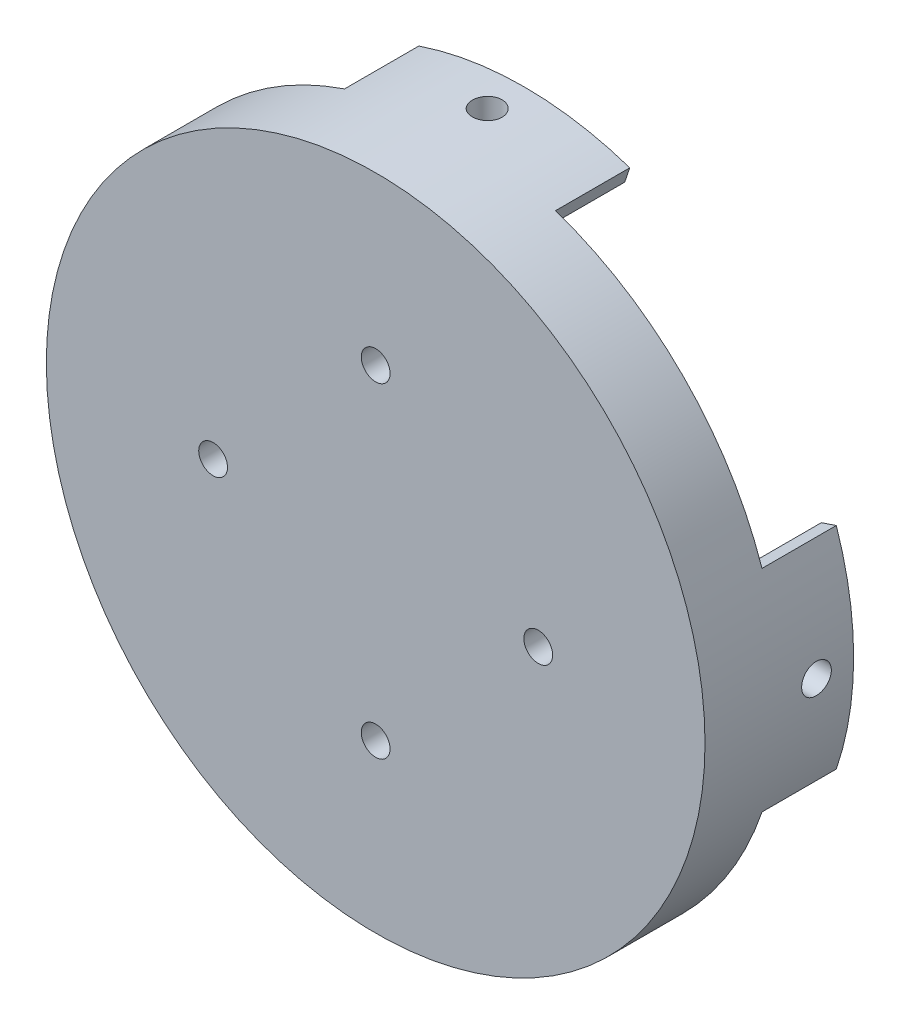
SolidWorks part; units mm, degrees
ref_plane "Front Plane" through (0, 0, 0) normal (0, 0, 1) x (1, 0, 0)
ref_plane "Top Plane" through (0, 0, 0) normal (0, 1, 0) x (1, 0, 0)
ref_plane "Right Plane" through (0, 0, 0) normal (1, 0, 0) x (0, 0, -1)
sketch "Sketch2" plane through (0, 0, 0) normal (0, 0, 1) x (1, 0, 0)
  circle A0 centre (0, 0) radius 45.0259
  circle A1 centre (0, -22.225) radius 1.9685
  circle A2 centre (-22.225, 0) radius 1.9685
  circle A3 centre (0, 22.225) radius 1.9685
  circle A4 centre (22.225, 0) radius 1.9685
  point P14 (0, 0)
  dimension "D2" = 3.937
  dimension "D1" = 22.225
  dimension "D3" = 4
extrude "Boss-Extrude1" add sketch "Sketch2" along normal blind 10.16
sketch "Sketch3" plane through (0, 0, 0) normal (0, 0, -1) x (-1, 0, 0)
  circle A0 centre (0, 22.225) radius 3.81
  circle A1 centre (22.225, 0) radius 3.81
  circle A2 centre (0, -22.225) radius 3.81
  circle A3 centre (-22.225, 0) radius 3.81
  point P12 (0, 0)
  dimension "D1" = 7.62
  dimension "D2" = 4
extrude "Cut-Extrude1" cut sketch "Sketch3" against normal blind 3.81
sketch "Sketch5" plane through (0, 0, 0) normal (0, 0, -1) x (-1, 0, 0)
  line L0 (41.6999, 5.08) -> (41.6999, -5.08)
  line L1 (41.6999, -5.08) -> (42.5601, -5.08)
  line L2 (40.6046, -13.7271) -> (42.6544, -14.4201)
  line L3 (42.1098, 0) -> (44.2948, 0) construction
  line L4 (40.6046, 13.7271) -> (42.6544, 14.4201)
  line L5 (41.6999, 5.08) -> (42.5601, 5.08)
  arc A0 (42.5601, -5.08) -> (40.6046, -13.7271) centre (0, 0) cw
  circle A1 centre (0, 0) radius 42.8622 construction
  circle A2 centre (0, 0) radius 45.0259 construction
  arc A3 (42.6544, -14.4201) -> (42.6544, 14.4201) centre (0, 0) ccw
  arc A4 (42.5601, 5.08) -> (40.6046, 13.7271) centre (0, 0) ccw
extrude "Boss-Extrude2" add sketch "Sketch5" along normal blind 10.16
sketch "Sketch6" plane through (-41.6999, 0, 0) normal (1, 0, 0) x (0, 0, -1)
  circle A0 centre (5.08, 0) radius 2.032
extrude "Cut-Extrude2" cut sketch "Sketch6" against normal blind 10.16
pattern_circular "CirPattern2" count 4 every 90 about axis through (0, 0, 0) along (0, 0, 1) of "Boss-Extrude2", "Cut-Extrude2"
